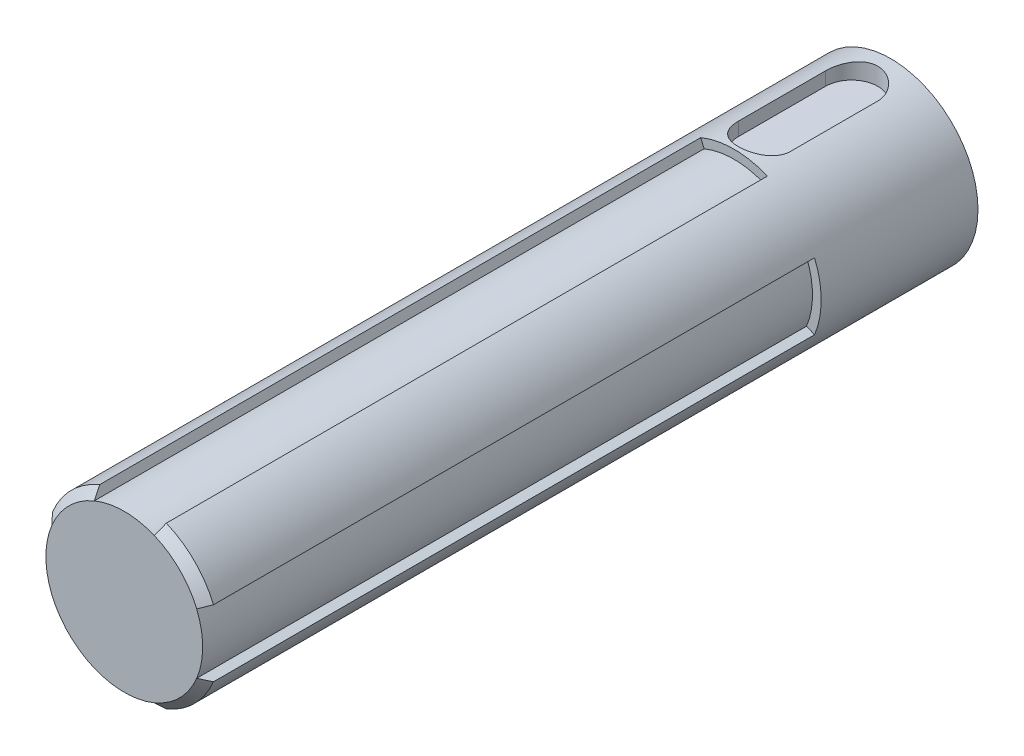
SolidWorks part; units mm, degrees
ref_plane "Alzado" through (0, 0, 0) normal (0, 0, 1) x (1, 0, 0)
ref_plane "Planta" through (0, 0, 0) normal (0, 1, 0) x (1, 0, 0)
ref_plane "Vista lateral" through (0, 0, 0) normal (1, 0, 0) x (0, 0, -1)
sketch "Croquis1" plane through (0, 0, 0) normal (0, 0, 1) x (1, 0, 0)
  circle A0 centre (0, 0) radius 10
  dimension "D1" = 20
extrude "Saliente-Extruir1" add sketch "Croquis1" along normal blind 88
chamfer "Chaflán1" distance 1 angle 45 1 edges at (10, 0, 88)
sketch "Croquis3" plane through (0, 0, 88) normal (0, 0, 1) x (1, 0, 0)
  line L0 (-10, 0) -> (10, 0) construction
  line L1 (0, 10) -> (0, -10) construction
  line L2 (-9.2388, 3.8268) -> (-8.3149, 3.4442)
  line L3 (-9.2388, -3.8268) -> (-8.3149, -3.4442)
  line L4 (-3.8268, -9.2388) -> (-3.4442, -8.3149)
  line L5 (3.8268, -9.2388) -> (3.4442, -8.3149)
  line L6 (8.3149, -3.4442) -> (9.2388, -3.8268)
  line L7 (8.3149, 3.4442) -> (9.2388, 3.8268)
  line L8 (3.4442, 8.3149) -> (3.8268, 9.2388)
  line L9 (-3.4442, 8.3149) -> (-3.8268, 9.2388)
  circle A0 centre (0, 0) radius 10 construction
  circle A1 centre (0, 0) radius 10
  circle A2 centre (0, 0) radius 9 construction
  circle A3 centre (0, 0) radius 9
  point P11 (0, 0)
  circle M1 centre (0, 0) radius 9
  dimension "D1" = 22.5
  dimension "D2" = 22.5
  dimension "D3" = 22.5
  dimension "D4" = 22.5
  dimension "D5" = 22.5
  dimension "D6" = 22.5
  dimension "D7" = 22.5
  dimension "D8" = 22.5
extrude "Cortar-Extruir1" cut sketch "Croquis3" against normal blind 70 contours L8 A1 L9 M1 | L6 A1 L7 M1 | L4 A1 L5 M1 | L2 A1 L3 M1
ref_plane "Plano1" through (0, 10, 0) normal (0, 1, 0) x (1, 0, 0)
sketch "Croquis4" plane through (0, 10, 0) normal (0, 1, 0) x (1, 0, 0)
  line L0 (0, -14.5) -> (0, -4.5) construction
  line L1 (-3, -14.5) -> (-3, -4.5)
  line L2 (3, -14.5) -> (3, -4.5)
  line L4 (10, 0) -> (-10, 0) construction
  arc A0 (-3, -14.5) -> (3, -14.5) centre (0, -14.5) ccw
  arc A1 (3, -4.5) -> (-3, -4.5) centre (0, -4.5) ccw
  point P3 (0, -9.5)
  dimension "D2" = 3
  dimension "D3" = 4.5
  dimension "D1" = 10
extrude "Cortar-Extruir5" cut sketch "Croquis4" against normal blind 2
